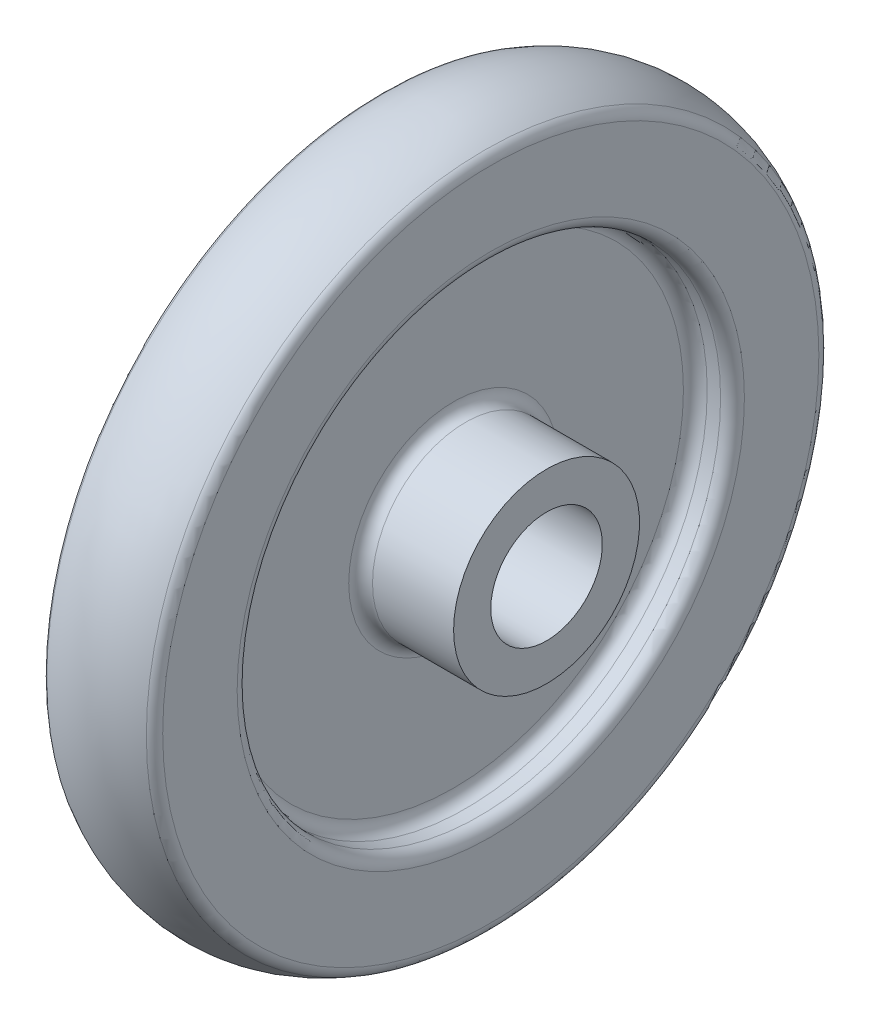
SolidWorks part; units mm, degrees
ref_plane "Front Plane" through (0, 0, 0) normal (0, 0, 1) x (1, 0, 0)
ref_plane "Top Plane" through (0, 0, 0) normal (0, 1, 0) x (1, 0, 0)
ref_plane "Right Plane" through (0, 0, 0) normal (1, 0, 0) x (0, 0, -1)
sketch "Sketch1" plane through (0, 0, 0) normal (0, 0, 1) x (1, 0, 0)
  line L0 (0, 0) -> (38.1, 0) construction
  line L1 (0, 9.525) -> (38.1, 9.525)
  line L2 (0, 15.875) -> (13.843, 15.875)
  line L3 (38.1, 9.525) -> (38.1, 15.875)
  line L4 (0, 9.525) -> (0, 15.875)
  line L5 (19.05, 6.35) -> (19.05, 38.1) construction
  line L6 (22.225, 17.907) -> (22.225, 39.243)
  line L7 (24.257, 41.275) -> (26.543, 41.275)
  line L8 (28.575, 43.307) -> (28.575, 56.0164)
  line L9 (15.875, 17.907) -> (15.875, 39.243)
  line L10 (13.843, 41.275) -> (11.557, 41.275)
  line L11 (9.525, 43.307) -> (9.525, 56.0164)
  line L12 (24.257, 15.875) -> (38.1, 15.875)
  line L13 (0, 15.875) -> (38.1, 15.875) construction
  line L14 (22.225, 6.35) -> (22.225, 38.1) construction
  arc A0 (27.5471, 57.783) -> (10.5529, 57.783) centre (19.05, 42.8332) ccw
  arc A1 (22.225, 39.243) -> (24.257, 41.275) centre (24.257, 39.243) cw
  arc A2 (26.543, 41.275) -> (28.575, 43.307) centre (26.543, 43.307) ccw
  arc A3 (22.225, 17.907) -> (24.257, 15.875) centre (24.257, 17.907) ccw
  arc A4 (15.875, 17.907) -> (13.843, 15.875) centre (13.843, 17.907) cw
  arc A5 (15.875, 39.243) -> (13.843, 41.275) centre (13.843, 39.243) ccw
  arc A6 (11.557, 41.275) -> (9.525, 43.307) centre (11.557, 43.307) cw
  arc A7 (9.525, 56.0164) -> (10.5529, 57.783) centre (11.557, 56.0164) cw
  arc A8 (28.575, 56.0164) -> (27.5471, 57.783) centre (26.543, 56.0164) ccw
  point P21 (22.225, 41.275)
  point P24 (28.575, 41.275)
  point P32 (15.875, 41.275)
  point P35 (9.525, 41.275)
  point P38 (9.525, 57.15)
  point P41 (28.575, 57.15)
  dimension "D6" = 2.032
  dimension "D1" = 38.1
  dimension "D4" = 25.4
  dimension "D2" = 9.525
  dimension "D3" = 6.35
  dimension "D5" = 3.175
revolve "Revolve1" add sketch "Sketch1" angle 360 about L0
